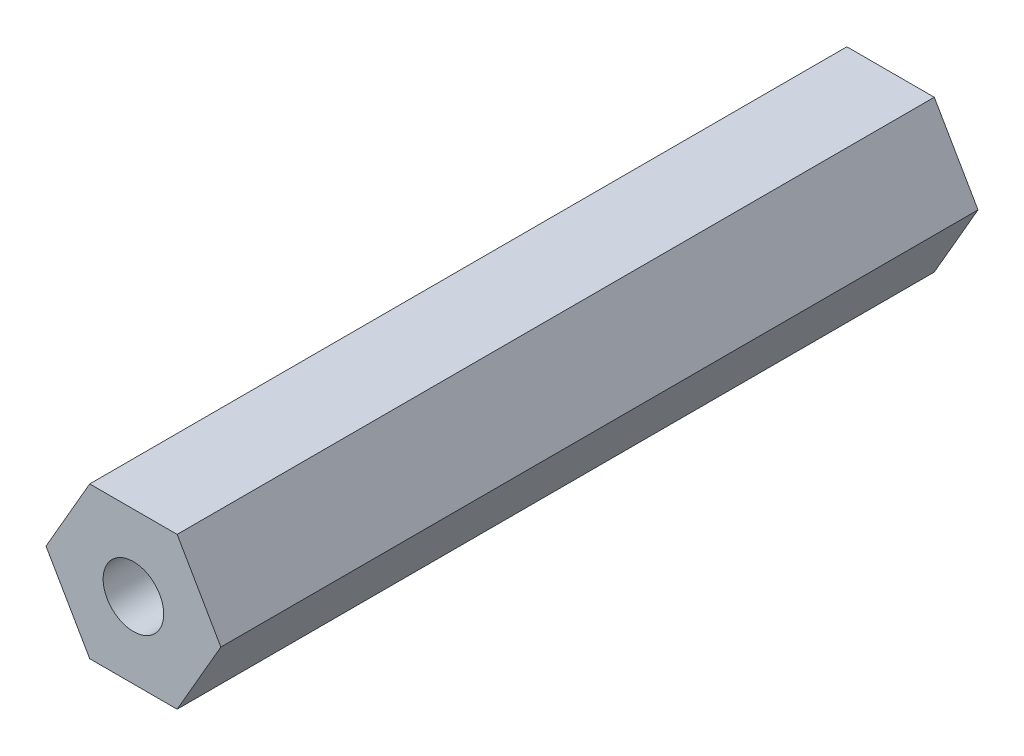
SolidWorks part; units mm, degrees
material "Copper"
ref_plane "Front Plane" through (0, 0, 0) normal (0, 0, 1) x (1, 0, 0)
ref_plane "Top Plane" through (0, 0, 0) normal (0, 1, 0) x (1, 0, 0)
ref_plane "Right Plane" through (0, 0, 0) normal (1, 0, 0) x (0, 0, -1)
sketch "Sketch1" plane through (0, 0, 0) normal (0, 0, 1) x (1, 0, 0)
  line L0 (0, 0) -> (2.8868, 0) construction
  line L1 (2.8868, 0) -> (1.4434, 2.5)
  line L2 (1.4434, 2.5) -> (-1.4434, 2.5)
  line L3 (-1.4434, 2.5) -> (-2.8868, 0)
  line L4 (-2.8868, 0) -> (-1.4434, -2.5)
  line L5 (-1.4434, -2.5) -> (1.4434, -2.5)
  line L6 (1.4434, -2.5) -> (2.8868, 0)
  circle A0 centre (0, 0) radius 2.5 construction
  dimension "D1" = 5
extrude "Boss-Extrude1" add sketch "Sketch1" along normal blind 25
sketch "Sketch2" plane through (0, 0, 25) normal (0, 0, 1) x (1, 0, 0)
  circle A0 centre (0, 0) radius 1
  dimension "D1" = 2
extrude "Cut-Extrude1" cut sketch "Sketch2" against normal through all
